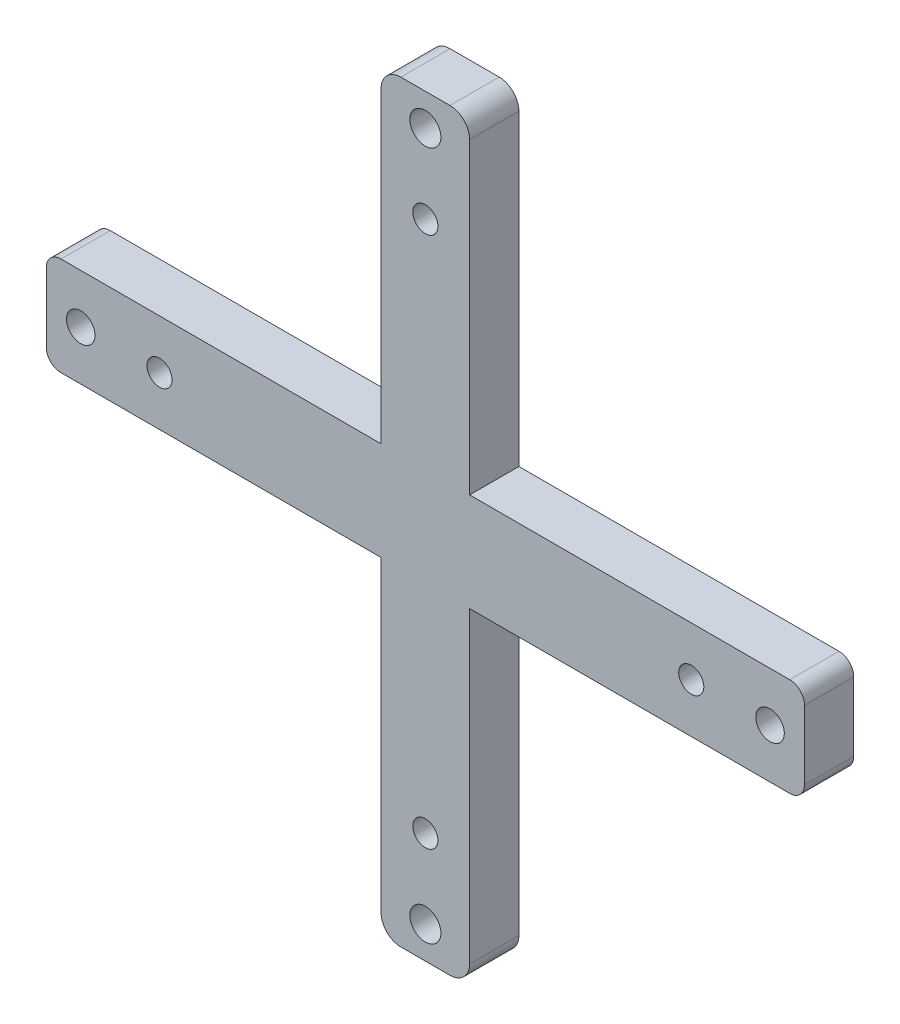
SolidWorks part; units mm, degrees
ref_plane "Front Plane" through (0, 0, 0) normal (0, 0, 1) x (1, 0, 0)
ref_plane "Top Plane" through (0, 0, 0) normal (0, 1, 0) x (1, 0, 0)
ref_plane "Right Plane" through (0, 0, 0) normal (1, 0, 0) x (0, 0, -1)
sketch "Sketch1" plane through (0, 0, 0) normal (0, 0, 1) x (1, 0, 0)
  line L1 (93.98, -12.7) -> (-93.98, -12.7)
  line L2 (97.79, -8.89) -> (97.79, 8.89)
  line L3 (93.98, 12.7) -> (-93.98, 12.7)
  line L4 (-97.79, -8.89) -> (-97.79, 8.89)
  line L5 (97.79, -12.7) -> (-97.79, 12.7) construction
  line L6 (97.79, 12.7) -> (-97.79, -12.7) construction
  arc A0 (97.79, 8.89) -> (93.98, 12.7) centre (93.98, 8.89) ccw
  arc A1 (93.98, -12.7) -> (97.79, -8.89) centre (93.98, -8.89) ccw
  arc A2 (-93.98, -12.7) -> (-97.79, -8.89) centre (-93.98, -8.89) cw
  arc A3 (-93.98, 12.7) -> (-97.79, 8.89) centre (-93.98, 8.89) ccw
  circle A4 centre (-88.9, 0) radius 3.683
  circle A5 centre (88.9, 0) radius 3.683
  point P0 (0, 0)
  dimension "D3" = 3.81
  dimension "D6" = 7.366
  dimension "D7" = 7.366
  dimension "D1" = 25.4
  dimension "D2" = 195.58
  dimension "D4" = 88.9
  dimension "D5" = 88.9
extrude "Boss-Extrude1" add sketch "Sketch1" along normal blind 12.7
sketch "Sketch3" plane through (0, 0, 12.7) normal (0, 0, 1) x (1, 0, 0)
  line L1 (-6.3354, -97.155) -> (6.3354, -97.155)
  line L2 (-11.4154, -92.075) -> (-11.4154, 92.075)
  line L3 (-6.3354, 97.155) -> (6.3354, 97.155)
  line L4 (11.4154, -92.075) -> (11.4154, 92.075)
  line L5 (-11.4154, -97.155) -> (11.4154, 97.155) construction
  line L6 (-11.4154, 97.155) -> (11.4154, -97.155) construction
  arc A0 (-6.3354, -97.155) -> (-11.4154, -92.075) centre (-6.3354, -92.075) cw
  arc A1 (6.3354, -97.155) -> (11.4154, -92.075) centre (6.3354, -92.075) ccw
  arc A2 (-11.4154, 92.075) -> (-6.3354, 97.155) centre (-6.3354, 92.075) cw
  arc A3 (6.3354, 97.155) -> (11.4154, 92.075) centre (6.3354, 92.075) cw
  circle A4 centre (0, 88.9) radius 4
  circle A5 centre (0, -88.9) radius 4
  point P0 (0, 0)
  dimension "D1" = 5.08
  dimension "D3" = 88.9
  dimension "D5" = 8
  dimension "D6" = 8
  dimension "D2" = 88.9
  dimension "D4" = 184.15
extrude "Boss-Extrude3" add sketch "Sketch3" against normal through all
sketch "Sketch2" plane through (0, 0, 0) normal (0, 0, -1) x (-1, 0, 0)
  circle A0 centre (-88.9, 0) radius 3.683
  circle A1 centre (88.9, 0) radius 3.683
  circle A2 centre (0, 88.9) radius 4
  circle A3 centre (0, -88.9) radius 4
extrude "Boss-Extrude2" add sketch "Sketch2" against normal blind 6.35
sketch "Sketch4" plane through (0, 0, 12.7) normal (0, 0, 1) x (1, 0, 0)
  circle A0 centre (-68.58, 0) radius 3.2385
  circle A1 centre (0, 68.58) radius 3.2385
  circle A2 centre (68.58, 0) radius 3.2385
  circle A3 centre (0, -68.58) radius 3.2385
  circle A4 centre (-88.9, 0) radius 3.683 construction
  circle A5 centre (0, 88.9) radius 4 construction
  circle A6 centre (88.9, 0) radius 3.683 construction
  circle A7 centre (0, -88.9) radius 4 construction
  dimension "D1" = 6.477
  dimension "D2" = 6.477
  dimension "D3" = 6.477
  dimension "D4" = 6.477
  dimension "D5" = 20.32
  dimension "D6" = 20.32
  dimension "D7" = 20.32
  dimension "D8" = 20.32
extrude "Cut-Extrude1" cut sketch "Sketch4" against normal through all
